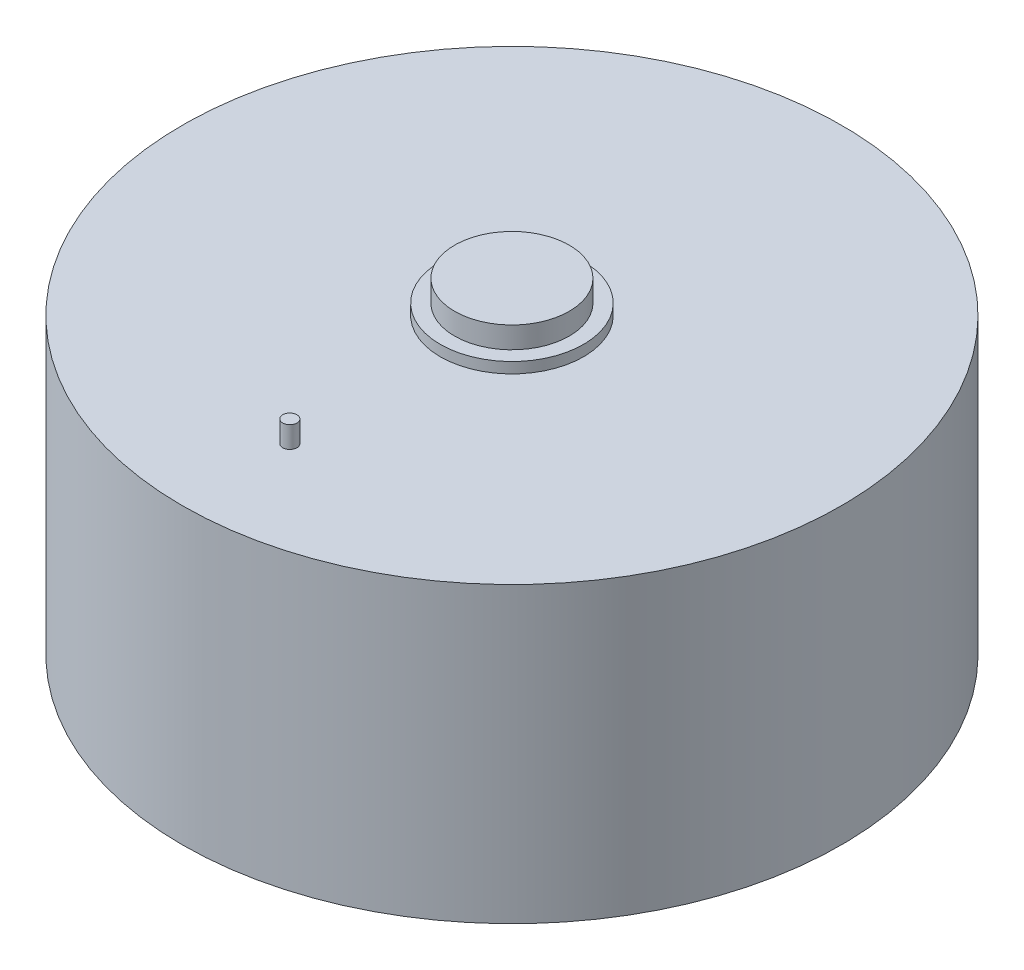
SolidWorks part; units mm, degrees
material "Plastique personnalisé"
ref_plane "Plan de face" through (0, 0, 0) normal (0, 0, 1) x (1, 0, 0)
ref_plane "Plan de dessus" through (0, 0, 0) normal (0, 1, 0) x (1, 0, 0)
ref_plane "Plan de droite" through (0, 0, 0) normal (1, 0, 0) x (0, 0, -1)
sketch "Esquisse1" plane through (0, 0, 0) normal (0, 1, 0) x (1, 0, 0)
  circle A0 centre (0, 0) radius 46
  dimension "D1" = 92
extrude "Boss.-Extru.1" add sketch "Esquisse1" along normal blind 41
ref_plane "Plan1" through (0, 41, 0) normal (0, 1, 0) x (1, 0, 0)
sketch "Esquisse2" plane through (0, 41, 0) normal (0, 1, 0) x (1, 0, 0)
  circle A0 centre (0, 0) radius 10
  dimension "D1" = 20
extrude "Boss.-Extru.2" add sketch "Esquisse2" along normal blind 1.5
ref_plane "Plan2" through (0, 42.5, 0) normal (0, 1, 0) x (1, 0, 0)
sketch "Esquisse3" plane through (0, 42.5, 0) normal (0, 1, 0) x (1, 0, 0)
  circle A1 centre (0, 0) radius 8
extrude "Boss.-Extru.3" add sketch "Esquisse3" along normal blind 3 contours A1
sketch "Esquisse4" plane through (0, 41, 0) normal (0, 1, 0) x (1, 0, 0)
  line L0 (0, 0) -> (0, -31)
  circle A0 centre (0, -31) radius 0.995
  dimension "D2" = 1.99
  dimension "D1" = 31
extrude "Boss.-Extru.4" add sketch "Esquisse4" along normal blind 3 contours A0
